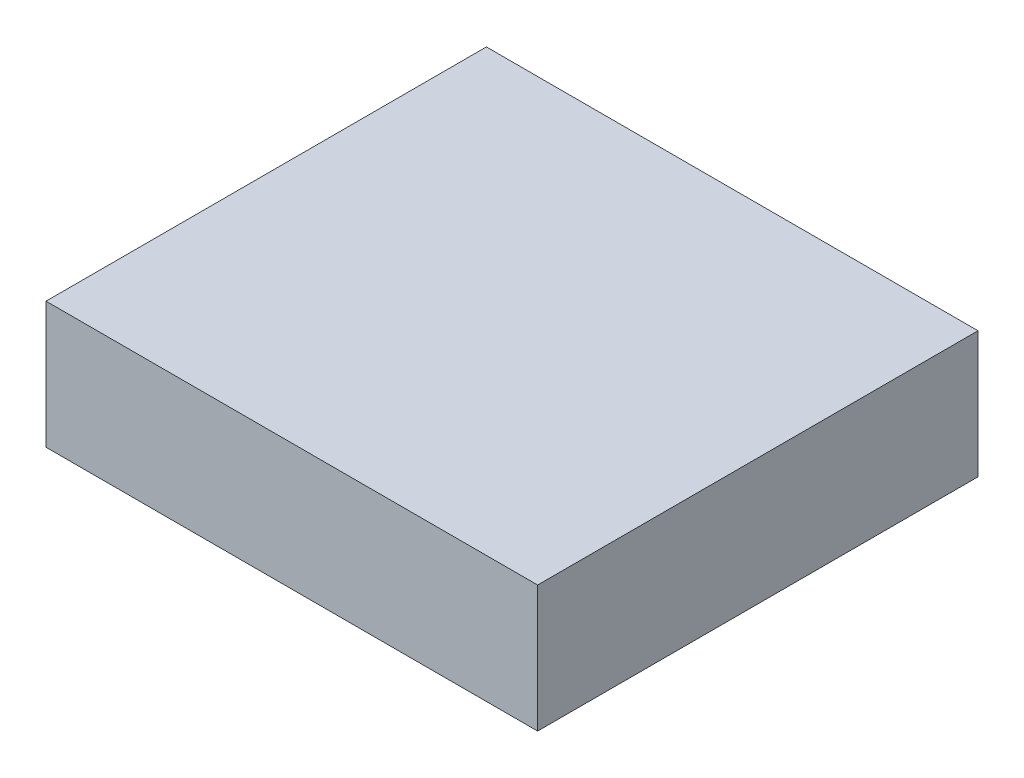
SolidWorks part; units mm, degrees
ref_plane "Front Plane" through (0, 0, 0) normal (0, 0, 1) x (1, 0, 0)
ref_plane "Top Plane" through (0, 0, 0) normal (0, 1, 0) x (1, 0, 0)
ref_plane "Right Plane" through (0, 0, 0) normal (1, 0, 0) x (0, 0, -1)
sketch "Sketch1" plane through (0, 0, 0) normal (0, 1, 0) x (1, 0, 0)
  line L1 (0, 0) -> (77.978, 0)
  line L2 (0, 0) -> (0, 69.85)
  line L3 (0, 69.85) -> (77.978, 69.85)
  line L4 (77.978, 0) -> (77.978, 69.85)
  dimension "D1" = 69.85
  dimension "D2" = 77.978
extrude "Boss-Extrude1" add sketch "Sketch1" along normal blind 20.066
